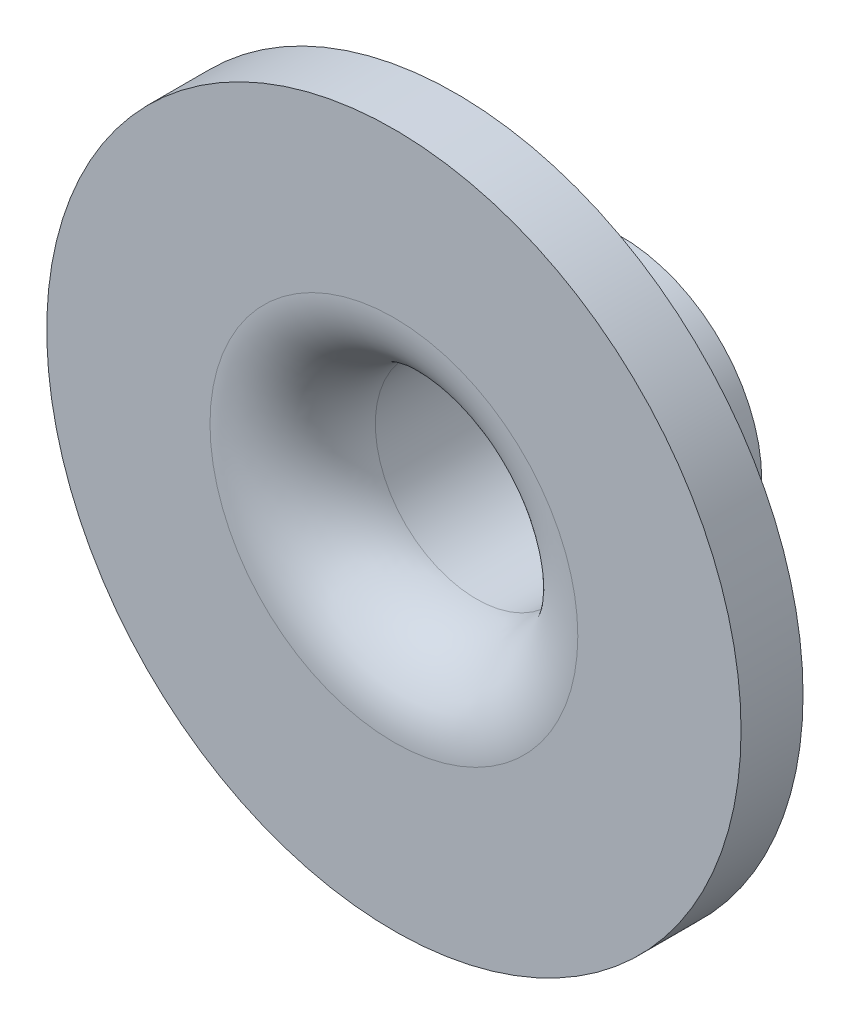
SolidWorks part; units mm, degrees
ref_plane "Front Plane" through (0, 0, 0) normal (0, 0, 1) x (1, 0, 0)
ref_plane "Top Plane" through (0, 0, 0) normal (0, 1, 0) x (1, 0, 0)
ref_plane "Right Plane" through (0, 0, 0) normal (1, 0, 0) x (0, 0, -1)
sketch "Sketch1" plane through (0, 0, 0) normal (0, 0, 1) x (1, 0, 0)
  circle A0 centre (0, 0) radius 2.45
  circle A1 centre (0, 0) radius 3.4
  dimension "D1" = 4.9
  dimension "D2" = 6.8
extrude "Boss-Extrude1" add sketch "Sketch1" along normal blind 5.5
sketch "Sketch2" plane through (0, 0, 5.5) normal (0, 0, 1) x (1, 0, 0)
  circle A0 centre (0, 0) radius 2.45 construction
  circle A1 centre (0, 0) radius 3.4
  circle A2 centre (0, 0) radius 3.4
  circle A3 centre (0, 0) radius 2.45
  circle A4 centre (0, 0) radius 8.4
  circle M2 centre (0, 0) radius 3.4
  dimension "D2" = 5
  dimension "D1" = 0
extrude "Boss-Extrude2" add sketch "Sketch2" against normal blind 1.5 contours A4 M2
fillet "Fillet1" radius 2 1 edges at (3.4, 0, 4)
fillet "Fillet2" radius 2 1 edges at (2.45, 0, 5.5)
sketch "Sketch3" [suppressed] plane through (0, 0, 4) normal (0, 0, -1) x (-1, 0, 0)
  circle A0 centre (0, 0) radius 10.4
  circle A1 centre (0, 0) radius 5.4 construction
  circle A2 centre (0, 0) radius 5.4
  dimension "D1" = 5
